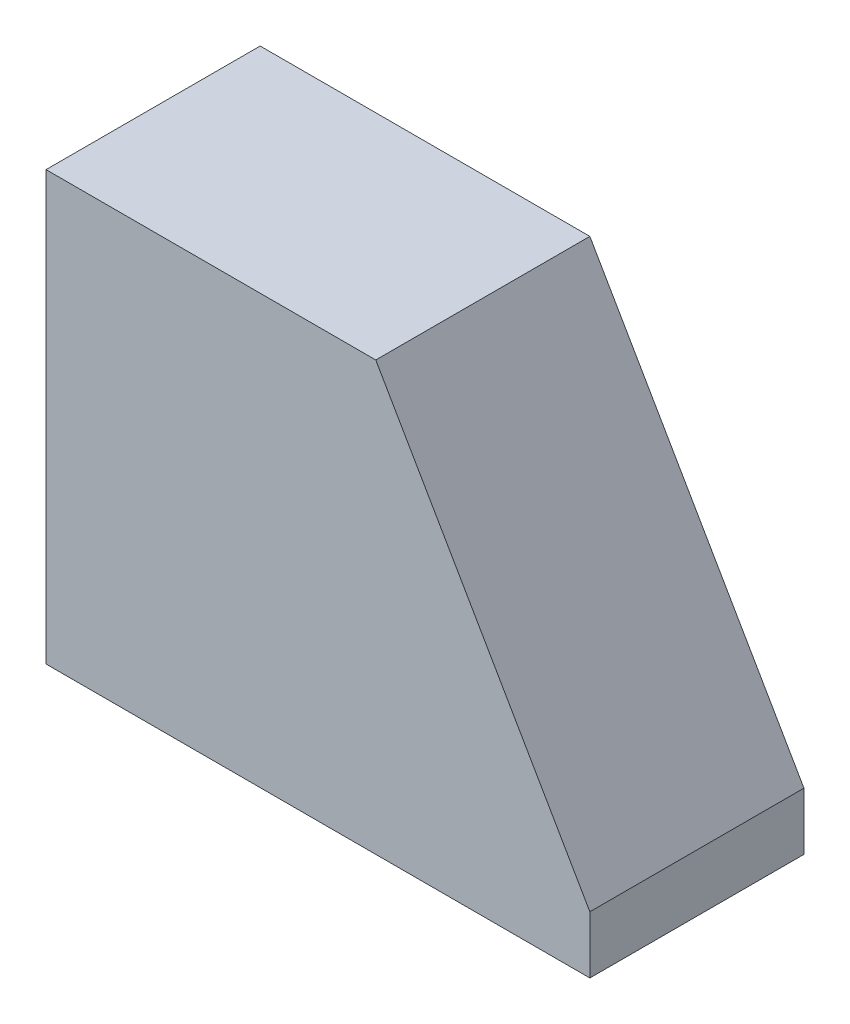
SolidWorks part; units mm, degrees
ref_plane "Front Plane" through (0, 0, 0) normal (0, 0, 1) x (1, 0, 0)
ref_plane "Top Plane" through (0, 0, 0) normal (0, 1, 0) x (1, 0, 0)
ref_plane "Right Plane" through (0, 0, 0) normal (1, 0, 0) x (0, 0, -1)
sketch "Sketch1" plane through (0, 0, 0) normal (1, 0, 0) x (0, 0, -1)
  line L1 (-5, -10) -> (5, -10)
  line L2 (-5, -10) -> (-5, 10)
  line L3 (-5, 10) -> (5, 10)
  line L4 (5, -10) -> (5, 10)
  line L5 (0, 10) -> (0, -10) construction
  line L6 (-5, 0) -> (5, 0) construction
  point P0 (0, 0)
  dimension "D1" = 20
  dimension "D2" = 10
extrude "Boss-Extrude1" add sketch "Sketch1" along normal blind 25.4
chamfer "Chamfer1" distance 10 angle 60 1 edges at (25.4, 10, 0)
